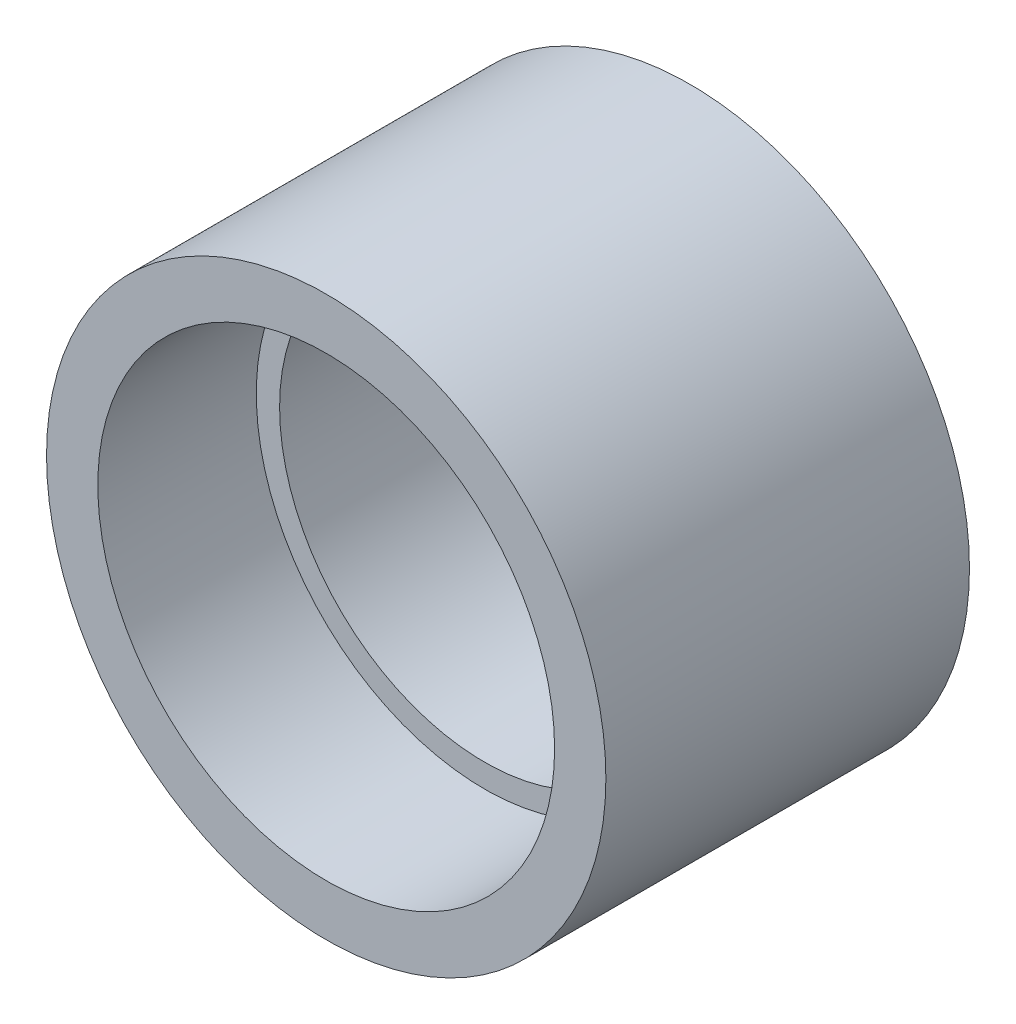
SolidWorks part; units mm, degrees
ref_plane "Alzado" through (0, 0, 0) normal (0, 0, 1) x (1, 0, 0)
ref_plane "Planta" through (0, 0, 0) normal (0, 1, 0) x (1, 0, 0)
ref_plane "Vista lateral" through (0, 0, 0) normal (1, 0, 0) x (0, 0, -1)
sketch "Croquis1" plane through (0, 0, 0) normal (0, 0, 1) x (1, 0, 0)
  circle A0 centre (0, 0) radius 15
  circle A1 centre (0, 0) radius 11
  dimension "D1" = 30
  dimension "D2" = 22
extrude "Saliente-Extruir1" add sketch "Croquis1" along normal blind 10 contours A1 | A0
sketch "Croquis2" plane through (0, 0, 0) normal (0, 0, -1) x (-1, 0, 0)
  circle A0 centre (0, 0) radius 15
extrude "Saliente-Extruir2" add sketch "Croquis2" along normal mid plane 2
sketch "Croquis3" plane through (0, 0, 10) normal (0, 0, 1) x (1, 0, 0)
  circle A0 centre (0, 0) radius 15
  circle A1 centre (0, 0) radius 12.25
  dimension "D1" = 24.5
extrude "Saliente-Extruir3" add sketch "Croquis3" along normal blind 8.5
